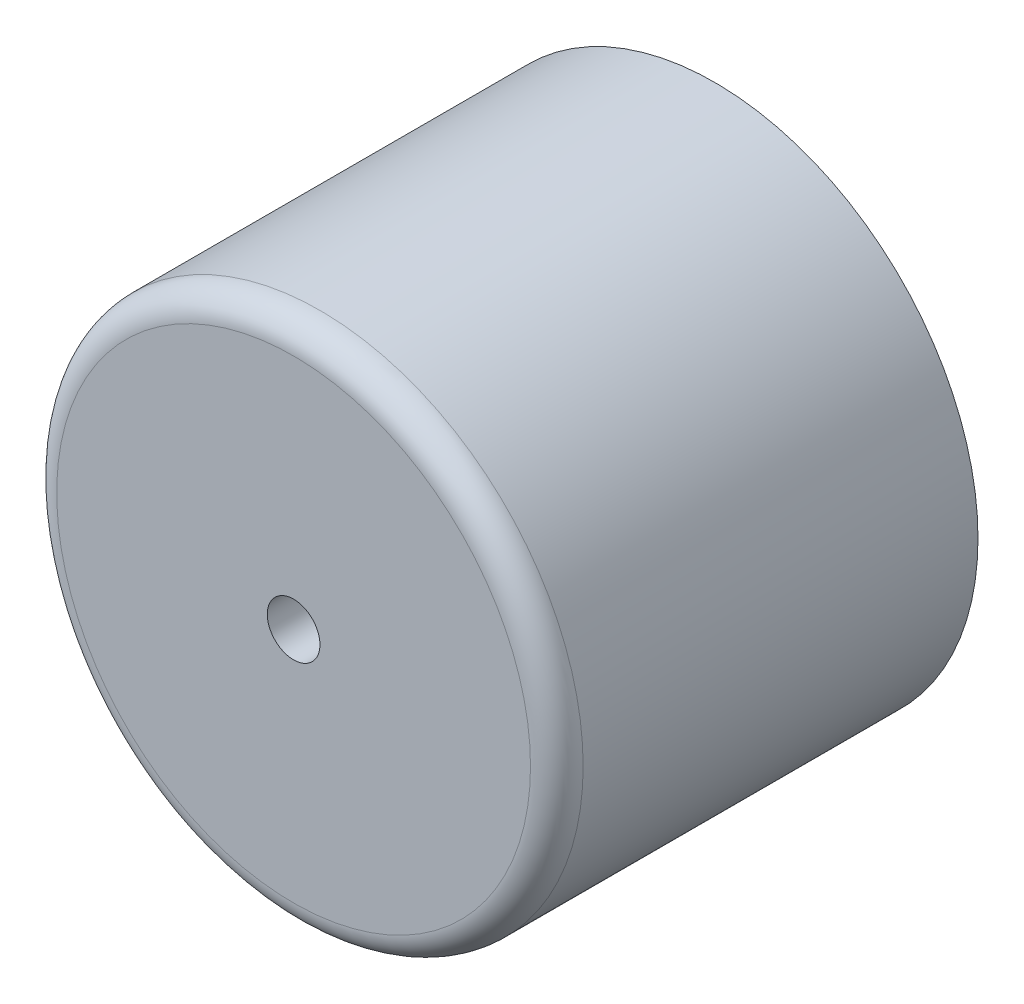
SolidWorks part; units mm, degrees
ref_plane "Front Plane" through (0, 0, 0) normal (0, 0, 1) x (1, 0, 0)
ref_plane "Top Plane" through (0, 0, 0) normal (0, 1, 0) x (1, 0, 0)
ref_plane "Right Plane" through (0, 0, 0) normal (1, 0, 0) x (0, 0, -1)
sketch "Sketch1" plane through (0, 0, 0) normal (0, 0, 1) x (1, 0, 0)
  circle A0 centre (0, 0) radius 50
  dimension "D1" = 100
extrude "Boss-Extrude1" add sketch "Sketch1" along normal blind 80
fillet "Fillet1" radius 5 1 edges at (50, 0, 80)
sketch "Sketch5" plane through (0, 0, 80) normal (0, 0, 1) x (1, 0, 0)
  circle A0 centre (0, 0) radius 5
  dimension "D1" = 10
extrude "Cut-Extrude2" cut sketch "Sketch5" against normal blind 80
